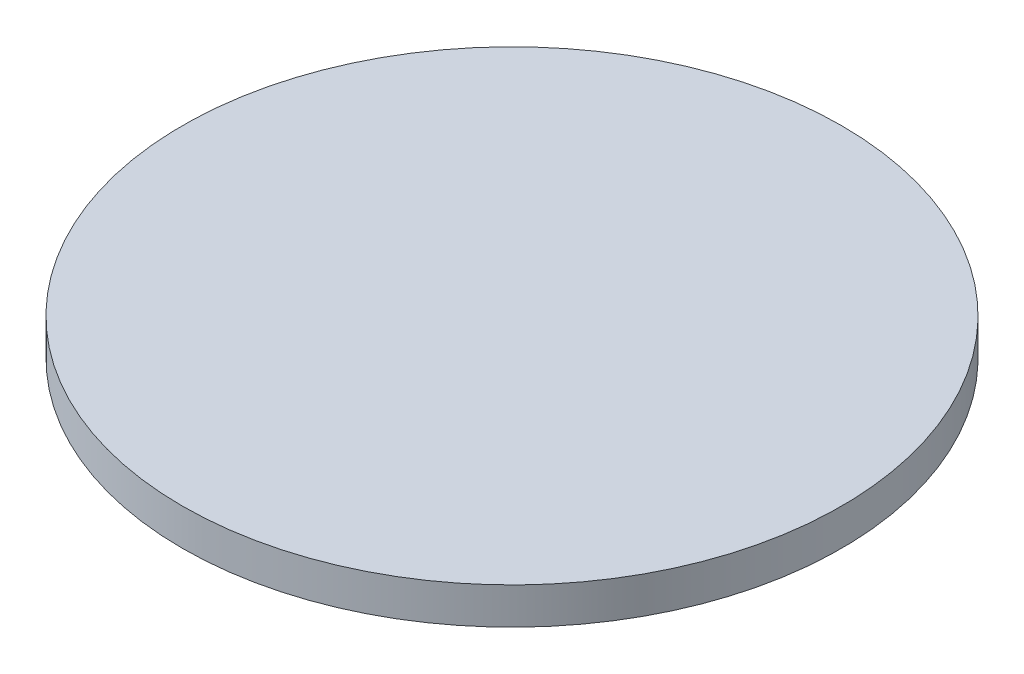
SolidWorks part; units mm, degrees
ref_plane "Front Plane" through (0, 0, 0) normal (0, 0, 1) x (1, 0, 0)
ref_plane "Top Plane" through (0, 0, 0) normal (0, 1, 0) x (1, 0, 0)
ref_plane "Right Plane" through (0, 0, 0) normal (1, 0, 0) x (0, 0, -1)
sketch "Sketch1" plane through (0, 0, 0) normal (0, 1, 0) x (1, 0, 0)
  circle A0 centre (0, 0) radius 90
  dimension "D1" = 180
extrude "Boss-Extrude1" add sketch "Sketch1" along normal blind 10
